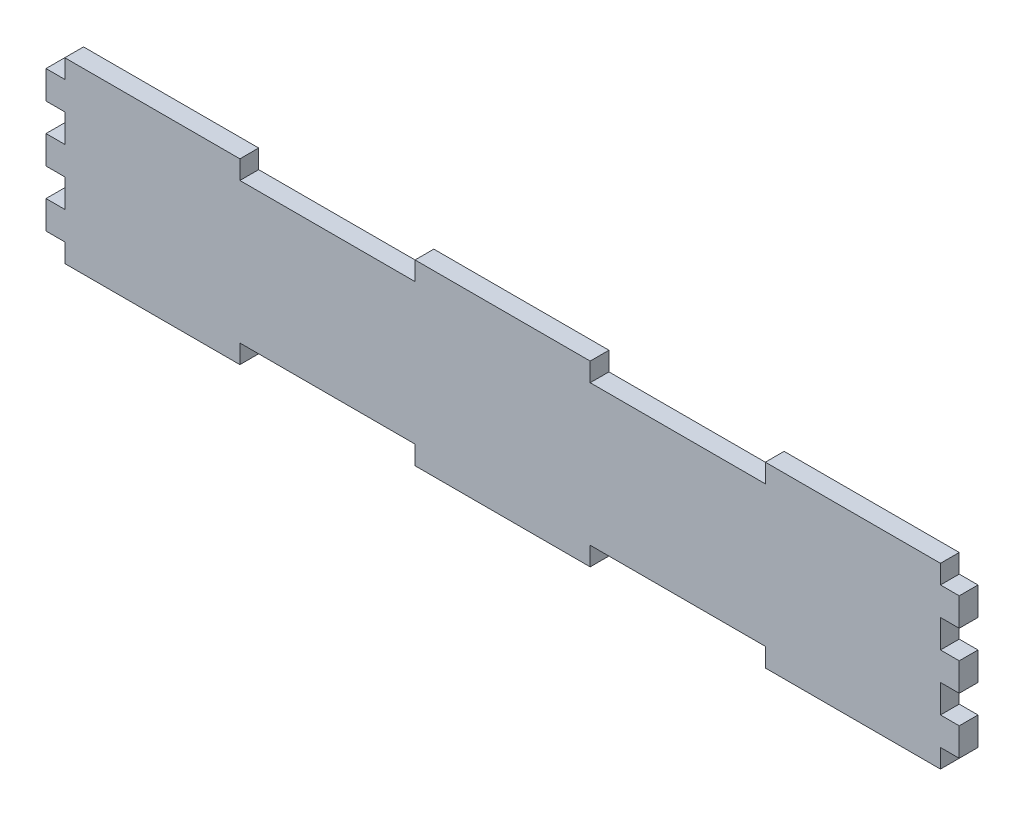
SolidWorks part; units mm, degrees
ref_plane "Front Plane" through (0, 0, 0) normal (0, 0, 1) x (1, 0, 0)
ref_plane "Top Plane" through (0, 0, 0) normal (0, 1, 0) x (1, 0, 0)
ref_plane "Right Plane" through (0, 0, 0) normal (1, 0, 0) x (0, 0, -1)
sketch "Sketch1" plane through (0, 0, 0) normal (0, 0, 1) x (1, 0, 0)
  line L0 (-59.8043, 30.7065) -> (-59.8043, 33.7065)
  line L1 (-31.8043, 30.7065) -> (-3.8043, 30.7065)
  line L2 (-59.8043, 26.2065) -> (-59.8043, 21.7065)
  line L3 (-31.8043, 8.2065) -> (-3.8043, 8.2065)
  line L4 (80.1957, 26.2065) -> (80.1957, 21.7065)
  line L5 (-59.8043, 33.7065) -> (-31.8043, 33.7065)
  line L6 (-31.8043, 33.7065) -> (-31.8043, 30.7065)
  line L7 (-3.8043, 30.7065) -> (-3.8043, 33.7065)
  line L8 (-3.8043, 33.7065) -> (24.1957, 33.7065)
  line L9 (24.1957, 33.7065) -> (24.1957, 30.7065)
  line L10 (52.1957, 30.7065) -> (52.1957, 33.7065)
  line L11 (52.1957, 33.7065) -> (80.1957, 33.7065)
  line L12 (80.1957, 33.7065) -> (80.1957, 30.7065)
  line L13 (-59.8043, 8.2065) -> (-59.8043, 5.2065)
  line L14 (-59.8043, 5.2065) -> (-31.8043, 5.2065)
  line L15 (-31.8043, 5.2065) -> (-31.8043, 8.2065)
  line L16 (-3.8043, 8.2065) -> (-3.8043, 5.2065)
  line L17 (-3.8043, 5.2065) -> (24.1957, 5.2065)
  line L18 (24.1957, 5.2065) -> (24.1957, 8.2065)
  line L19 (52.1957, 8.2065) -> (52.1957, 5.2065)
  line L20 (52.1957, 5.2065) -> (80.1957, 5.2065)
  line L21 (80.1957, 5.2065) -> (80.1957, 8.2065)
  line L22 (24.1957, 30.7065) -> (52.1957, 30.7065)
  line L23 (24.1957, 8.2065) -> (52.1957, 8.2065)
  line L24 (-59.8043, 30.7065) -> (-62.8043, 30.7065)
  line L25 (-62.8043, 30.7065) -> (-62.8043, 26.2065)
  line L26 (-62.8043, 26.2065) -> (-59.8043, 26.2065)
  line L27 (-59.8043, 21.7065) -> (-62.8043, 21.7065)
  line L28 (-62.8043, 21.7065) -> (-62.8043, 17.2065)
  line L29 (-62.8043, 17.2065) -> (-59.8043, 17.2065)
  line L30 (-59.8043, 12.7065) -> (-62.8043, 12.7065)
  line L31 (-62.8043, 12.7065) -> (-62.8043, 8.2065)
  line L32 (-62.8043, 8.2065) -> (-59.8043, 8.2065)
  line L33 (80.1957, 30.7065) -> (83.1957, 30.7065)
  line L34 (83.1957, 30.7065) -> (83.1957, 26.2065)
  line L35 (83.1957, 26.2065) -> (80.1957, 26.2065)
  line L36 (80.1957, 21.7065) -> (83.1957, 21.7065)
  line L37 (83.1957, 21.7065) -> (83.1957, 17.2065)
  line L38 (83.1957, 17.2065) -> (80.1957, 17.2065)
  line L39 (80.1957, 12.7065) -> (83.1957, 12.7065)
  line L40 (83.1957, 12.7065) -> (83.1957, 8.2065)
  line L41 (83.1957, 8.2065) -> (80.1957, 8.2065)
  line L42 (-59.8043, 17.2065) -> (-59.8043, 12.7065)
  line L43 (80.1957, 17.2065) -> (80.1957, 12.7065)
  dimension "D1" = 140
  dimension "D2" = 28
  dimension "D3" = 3
  dimension "D5" = 28
  dimension "D6" = 3
  dimension "D8" = 22.5
  dimension "D9" = 3
  dimension "D10" = 4.5
  dimension "D12" = 3
  dimension "D13" = 4.5
  dimension "D4" = 3
  dimension "D7" = 3
  dimension "D11" = 3
  dimension "D14" = 3
extrude "Boss-Extrude1" add sketch "Sketch1" along normal blind 3
